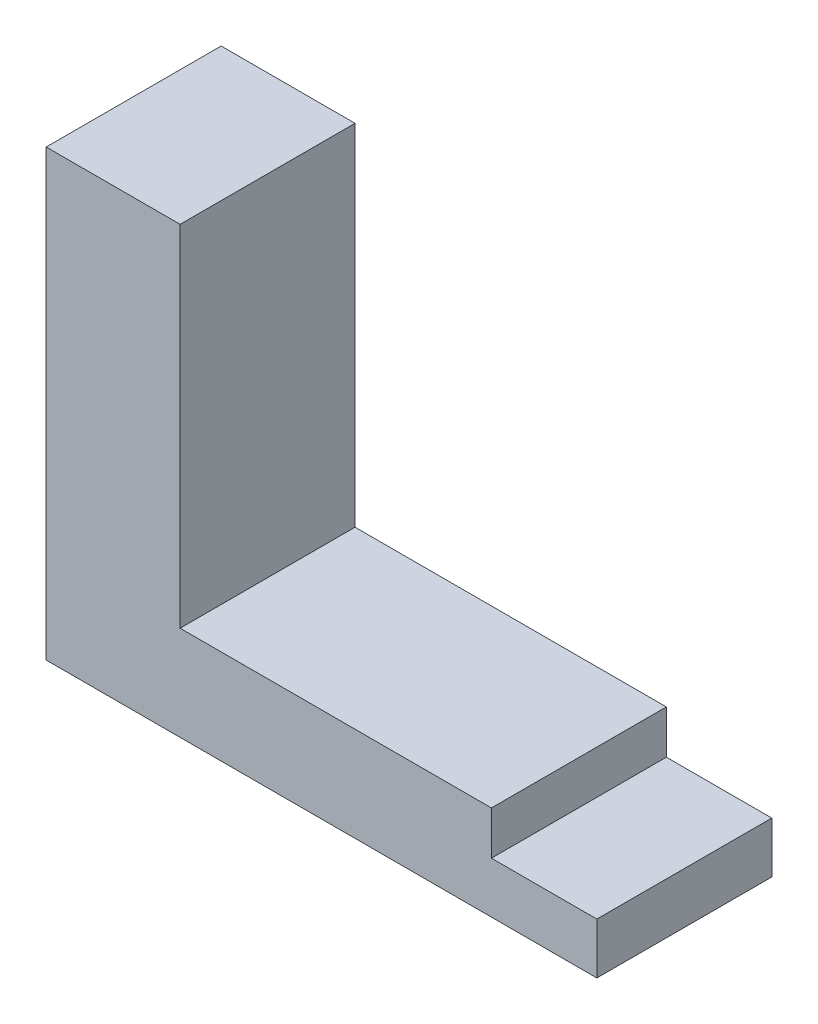
SolidWorks part; units mm, degrees
ref_plane "Plan de face" through (0, 0, 0) normal (0, 0, 1) x (1, 0, 0)
ref_plane "Plan de dessus" through (0, 0, 0) normal (0, 1, 0) x (1, 0, 0)
ref_plane "Plan de droite" through (0, 0, 0) normal (1, 0, 0) x (0, 0, -1)
sketch "Esquisse1" plane through (0, 0, 0) normal (0, 0, 1) x (1, 0, 0)
  line L0 (0, 0) -> (0, 50.803)
  line L1 (0, 50.803) -> (15.3079, 50.803)
  line L2 (15.3079, 50.803) -> (15.3079, 10.8112)
  line L3 (15.3079, 10.8112) -> (50.8987, 10.8112)
  line L4 (50.8987, 10.8112) -> (50.8987, 5.8361)
  line L5 (50.8987, 5.8361) -> (62.9536, 5.8361)
  line L6 (62.9536, 5.8361) -> (62.9536, 0)
  line L7 (62.9536, 0) -> (0, 0)
extrude "Boss.-Extru.1" add sketch "Esquisse1" along normal blind 20
